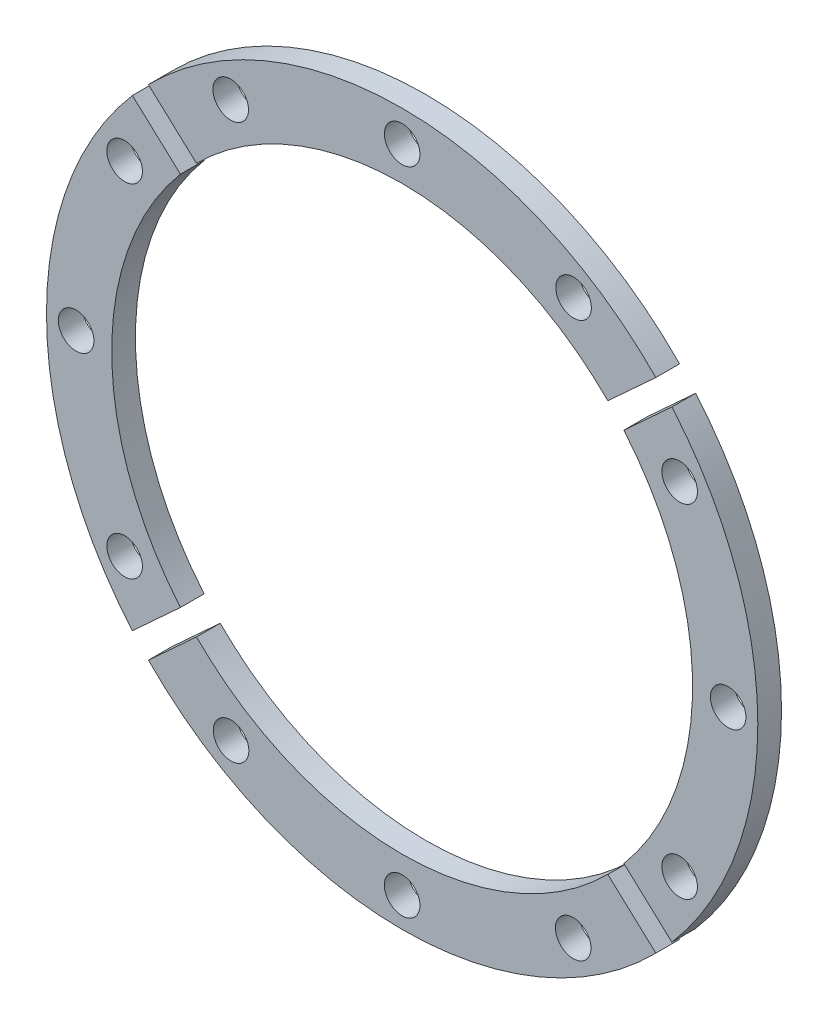
SolidWorks part; units mm, degrees
material "AISI 1020"
ref_plane "Ön Düzlem" through (0, 0, 0) normal (0, 0, 1) x (1, 0, 0)
ref_plane "Üst Düzlem" through (0, 0, 0) normal (0, 1, 0) x (1, 0, 0)
ref_plane "Sağ Düzlem" through (0, 0, 0) normal (1, 0, 0) x (0, 0, -1)
sketch "Çizim1" plane through (0, 0, 0) normal (0, 0, 1) x (1, 0, 0)
  line L0 (0, 300) -> (0, 245) construction
  line L1 (-300, 0) -> (-245, 0) construction
  line L3 (-214.1386, 210.3441) -> (-173.4891, 172.9929)
  line L4 (-227.6706, 195.6172) -> (-187.0211, 158.2659)
  line L5 (227.6706, 195.6172) -> (187.0211, 158.2659)
  line L7 (214.1386, 210.3441) -> (173.4891, 172.9929)
  line L9 (227.6706, -195.6172) -> (187.0211, -158.2659)
  line L11 (214.1386, -210.3441) -> (173.4891, -172.9929)
  line L12 (-214.1386, -210.3441) -> (-173.4891, -172.9929)
  line L14 (-227.6706, -195.6172) -> (-187.0211, -158.2659)
  line L17 (245, 0) -> (300, 0) construction
  line L19 (0, -245) -> (0, -300) construction
  arc A0 (-214.0158, -210.2313) -> (214.0158, -210.2313) centre (0, 0) ccw
  arc A1 (-173.4891, -172.9929) -> (173.4891, -172.9929) centre (0, 0) ccw
  arc A2 (209.128, -178.5791) -> (195.596, -193.306) centre (0, 0) ccw construction
  circle A3 centre (0, 273.8042) radius 15
  circle A4 centre (-275, 0) radius 15
  circle A5 centre (275, 0) radius 15
  circle A6 centre (0, -275) radius 15
  circle A7 centre (144.3137, -234.0909) radius 15
  circle A8 centre (-144.3137, -234.0909) radius 15
  circle A9 centre (-234.0909, -144.3137) radius 15
  circle A10 centre (-234.0909, 144.3137) radius 15
  circle A11 centre (-144.5989, 233.9149) radius 15
  circle A12 centre (144.5989, 233.9149) radius 15
  circle A13 centre (234.0909, 144.3137) radius 15
  circle A14 centre (234.0909, -144.3137) radius 15
  arc A15 (187.0211, -158.2659) -> (187.0211, 158.2659) centre (0, 0) ccw
  arc A16 (227.5479, -195.5044) -> (227.5479, 195.5044) centre (0, 0) ccw
  arc A17 (-187.0211, 158.2659) -> (-187.0211, -158.2659) centre (0, 0) ccw
  arc A18 (-227.5479, 195.5044) -> (-227.5479, -195.5044) centre (0, 0) ccw
  arc A19 (214.0158, 210.2313) -> (-214.0158, 210.2313) centre (0, 0) ccw
  arc A20 (173.4891, 172.9929) -> (-173.4891, 172.9929) centre (0, 0) ccw
  dimension "D1" = 600
  dimension "D2" = 490
  dimension "D3" = 550
  dimension "D4" = 30
  dimension "D5" = 150
  dimension "D6" = 150
  dimension "D7" = 150
  dimension "D8" = 150
  dimension "D9" = 150
  dimension "D10" = 150
  dimension "D11" = 150
  dimension "D12" = 150
extrude "Yükseklik-Ekstrüzyon1" add sketch "Çizim1" along normal blind 20 contours L4 A18 L14 A17 A4 A9 A10 | A20 L7 A19 L3 A12 A11 A3 | L9 A16 L5 A15 A5 A13 A14 | A1 L12 A0 L11 A8 A7 A6
